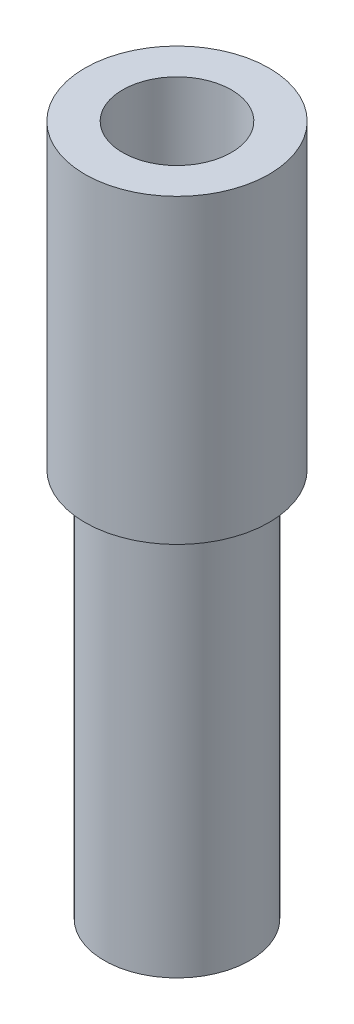
SolidWorks part; units mm, degrees
ref_plane "정면" through (0, 0, 0) normal (0, 0, 1) x (1, 0, 0)
ref_plane "윗면" through (0, 0, 0) normal (0, 1, 0) x (1, 0, 0)
ref_plane "우측면" through (0, 0, 0) normal (1, 0, 0) x (0, 0, -1)
sketch "스케치1" plane through (0, 0, 0) normal (1, 0, 0) x (0, 0, -1)
  line L0 (0, 0) -> (5.9045, 0) construction
  line L1 (5.9045, 0) -> (7.9045, 0)
  line L2 (7.9045, 0) -> (7.9045, 42.2544)
  line L3 (7.9045, 42.2544) -> (10, 42.2544)
  line L4 (10, 42.2544) -> (10, 75)
  line L5 (10, 75) -> (5.9045, 75)
  line L6 (5.9045, 75) -> (5.9045, 6.7624)
  line L7 (5.9045, 6.7624) -> (4, 6.7624)
  line L8 (4, 6.7624) -> (4, 4.9687)
  line L9 (4, 4.9687) -> (5.9045, 4.9687)
  line L10 (5.9045, 4.9687) -> (5.9045, 0)
  line L11 (0, 0) -> (0, 75) construction
  dimension "D1" = 20
  dimension "D2" = 8
  dimension "D3" = 75
  dimension "D4" = 2
revolve "회전1" add sketch "스케치1" angle 360 about L11
